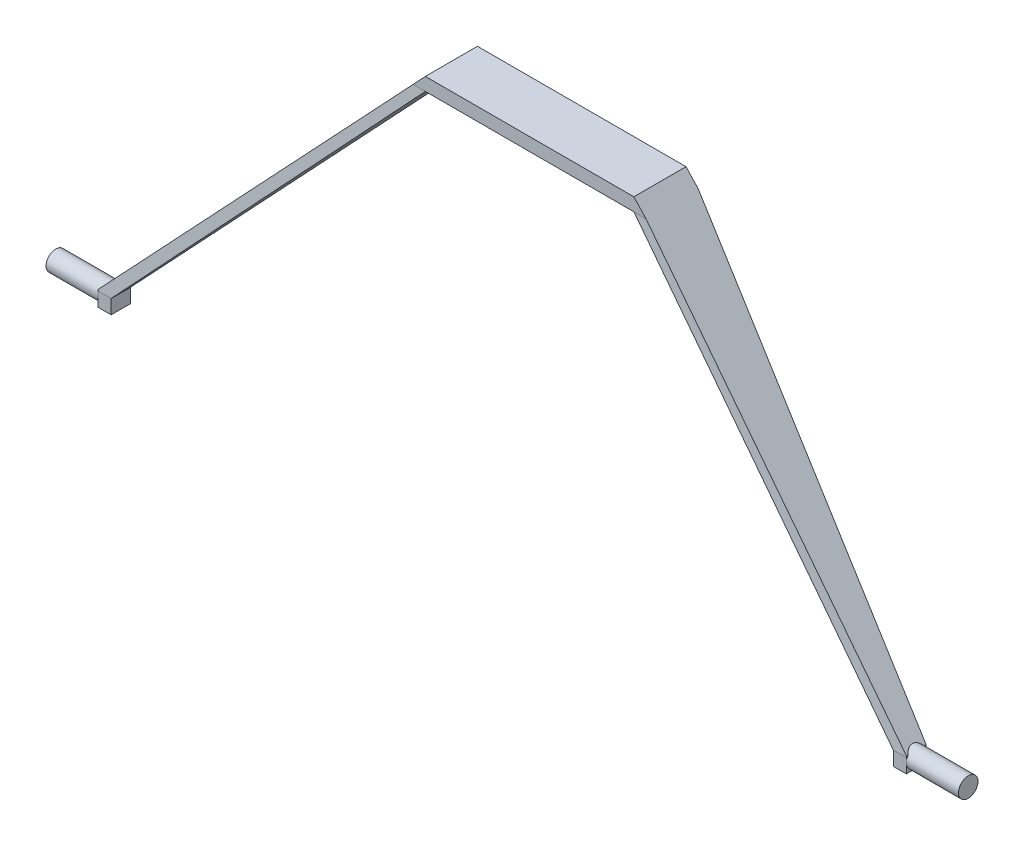
SolidWorks part; units mm, degrees
ref_plane "Front" through (0, 0, 0) normal (0, 0, 1) x (1, 0, 0)
ref_plane "Top" through (0, 0, 0) normal (0, 1, 0) x (1, 0, 0)
ref_plane "Right" through (0, 0, 0) normal (1, 0, 0) x (0, 0, -1)
sketch "Sketch12" plane through (0, 0, 0) normal (0, 0, 1) x (1, 0, 0)
  line L0 (-203.2, 241.3) -> (203.2, 241.3)
  line L1 (0, 241.3) -> (0, -425.45) construction
  line L2 (-203.2, 241.3) -> (-787.4717, -383.6692)
  line L3 (-787.4717, -383.6692) -> (-787.4717, -424.3092)
  line L4 (-787.4717, -424.3092) -> (-762.0717, -424.3092)
  line L5 (-762.0717, -424.3092) -> (-762.0717, -386.2092)
  line L6 (-762.0717, -386.2092) -> (-203.2, 215.9)
  line L7 (-203.2, 215.9) -> (203.2, 215.9)
  line L9 (762.0717, -386.2092) -> (203.2, 215.9)
  line L10 (762.0717, -424.3092) -> (762.0717, -386.2092)
  line L11 (787.4717, -424.3092) -> (762.0717, -424.3092)
  line L12 (787.4717, -383.6692) -> (787.4717, -424.3092)
  line L13 (203.2, 241.3) -> (787.4717, -383.6692)
  point P14 (0, 215.9)
  dimension "D1" = 666.75
  dimension "D2" = 40.64
  dimension "D3" = 25.4
  dimension "D4" = 38.1
extrude "Boss-Extrude6" add sketch "Sketch12" along normal blind 53.34 and the other way blind 101.6
sketch "Sketch13" plane through (787.4717, 0, 0) normal (1, 0, 0) x (0, 0, -1)
  line L0 (-53.34, -424.3092) -> (-53.34, -383.6692) construction
  line L1 (101.6, -424.3092) -> (-53.34, -424.3092) construction
  circle A0 centre (-34.29, -405.2592) radius 19.05
  dimension "D1" = 38.1
  dimension "D2" = 19.05
  dimension "D3" = 19.05
sketch "Sketch14" plane through (0, 0, 0) normal (1, 0, 0) x (0, 0, -1)
  line L0 (-53.34, 241.3) -> (0, 241.3) construction
  line L1 (101.6, 241.3) -> (-53.34, 241.3) construction
  line L2 (0, 241.3) -> (0, 215.9)
  line L5 (-53.34, -386.2092) -> (-15.24, -386.2092) construction
  line L6 (101.6, -386.2092) -> (-53.34, -386.2092) construction
  line L7 (0, 215.9) -> (-53.34, -386.2092)
  line L8 (-53.34, -386.2092) -> (-53.34, 241.3)
  line L9 (101.6, 215.9) -> (-15.24, -386.2092)
  line L10 (-15.24, -386.2092) -> (-15.24, -424.3092)
  line L11 (101.6, -424.3092) -> (-53.34, -424.3092) construction
  line L12 (-15.24, -424.3092) -> (101.6, -424.3092)
  line L13 (101.6, -424.3092) -> (101.6, 215.9)
  line L14 (-53.34, 241.3) -> (0, 241.3)
  dimension "D1" = 53.34
  dimension "D2" = 38.1
extrude "Cut-Extrude8" cut sketch "Sketch14" against normal up to surface and the other way up to surface up to face at (-495.3358, -71.1846, -24.13) other way up to face at (495.3358, -71.1846, -24.13)
ref_plane "Plane1" through (-762.0717, 0, 0) normal (-1, 0, 0) x (0, 0, 1)
sketch "Sketch15" plane through (-762.0717, 0, 0) normal (-1, 0, 0) x (0, 0, 1)
  line L0 (34.29, -405.2592) -> (34.29, -394.8452) construction
  line L1 (53.34, -386.2092) -> (53.34, -424.3092) construction
  circle A0 centre (34.29, -394.8452) radius 19.05
  dimension "D2" = 38.1
  dimension "D3" = 19.05
  dimension "D1" = 10.414
extrude "Boss-Extrude8" add sketch "Sketch15" along normal blind 127
mirror "Mirror2" about plane through (0, 0, 0) normal (1, 0, 0) of "Boss-Extrude8"
sketch "Sketch16" plane through (-762.0717, 0, 0) normal (-1, 0, 0) x (0, 0, 1)
  line L0 (15.24, -424.3092) -> (15.24, -394.8452) construction
  line L1 (15.24, -413.8952) -> (53.34, -413.8952)
  line L2 (15.24, -413.8952) -> (15.24, -424.3092)
  line L3 (15.24, -424.3092) -> (53.34, -424.3092)
  line L4 (53.34, -413.8952) -> (53.34, -424.3092)
extrude "Cut-Extrude9" cut sketch "Sketch16" along normal up to surface and the other way up to surface up to face at (-787.4717, -414.3397, 34.29) other way up to face at (787.4717, -414.3397, 34.29)
